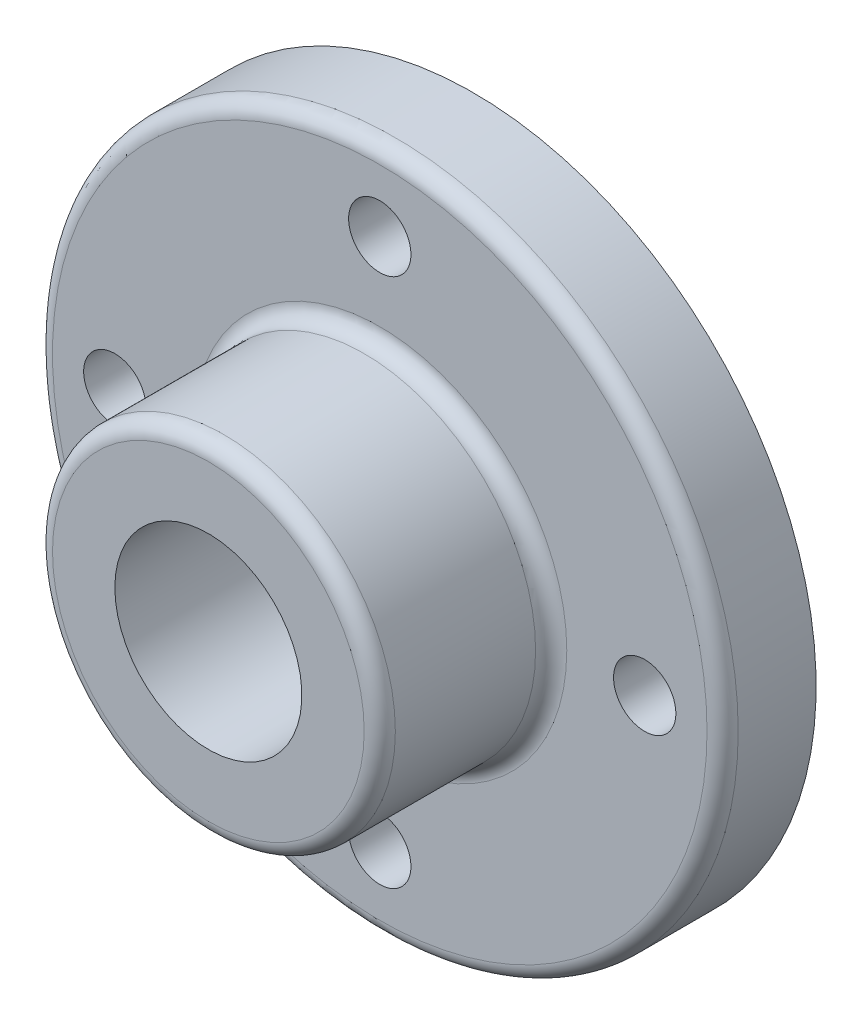
SolidWorks part; units mm, degrees
material "6063-T6"
ref_plane "Plane1" through (0, 0, 0) normal (0, 0, 1) x (1, 0, 0)
ref_plane "Plane2" through (0, 0, 0) normal (0, 1, 0) x (1, 0, 0)
ref_plane "Plane3" through (0, 0, 0) normal (1, 0, 0) x (0, 0, -1)
sketch "Esquisse1" plane through (0, 0, 0) normal (1, 0, 0) x (0, 0, -1)
  line L0 (0, 19.05) -> (0, 69.85)
  line L1 (0, 69.85) -> (-19.05, 69.85)
  line L2 (-19.05, 69.85) -> (-19.05, 34.925)
  line L3 (-19.05, 34.925) -> (-53.975, 34.925)
  line L4 (-53.975, 34.925) -> (-53.975, 19.05)
  line L5 (-53.975, 19.05) -> (0, 19.05)
  line L6 (-48.3195, 0) -> (0, 0) construction
  dimension "D1" = 19.05
  dimension "D2" = 19.05
  dimension "D3" = 69.85
  dimension "D4" = 139.7
  dimension "D5" = 53.975
revolve "Base-Révolution" add sketch "Esquisse1" angle 360 about L6
hole_wizard "Dégagement 22" positions "Esquisse6" profile "Esquisse5" hole size "2" standard "Ansi Inch" end condition through all
sketch "Esquisse6" plane through (0, 0, 19.05) normal (0, 0, 1) x (1, 0, 0)
  circle A0 centre (0, 0) radius 69.85 construction
  point P0 (0, 53.975)
  dimension "D1" = 53.975
sketch "Esquisse5" plane through (0, 53.975, 19.05) normal (1, 0, 0) x (0, -1, 0)
  line L0 (0, 0) -> (0, 19.05)
  line L1 (0, 19.05) -> (6.35, 19.05)
  line L2 (6.35, 19.05) -> (6.35, 0)
  line L5 (6.35, 0) -> (0, 0)
  line L11 (0, -6.35) -> (0, 107.95) construction
  dimension "Diamètre du perçage jusqu'au prochain" = 12.7
  dimension "Profondeur du perçage jusqu'au prochain" = 19.05
pattern_circular "Répétition circulaire1" count 4 every 90 about axis through (0, 0, 0) along (0, 0, 1) of "Dégagement 22"
fillet "Congé1" radius 3.175 3 edges at (-34.925, 0, 53.975) (-34.925, 0, 19.05) (-69.85, 0, 19.05)
